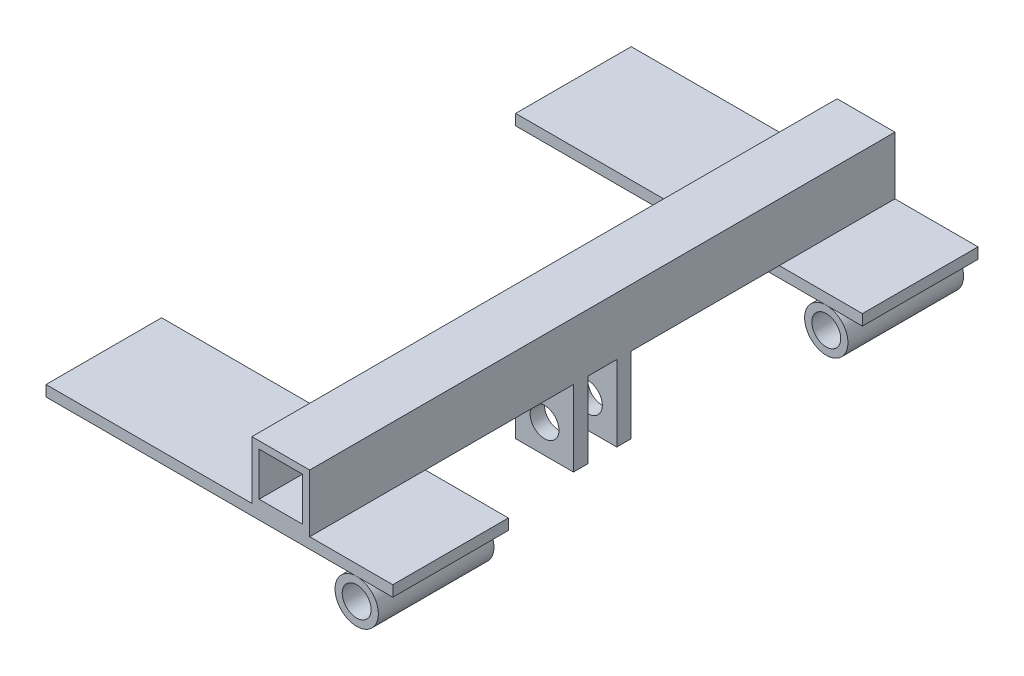
SolidWorks part; units mm, degrees
ref_plane "Front" through (0, 0, 0) normal (0, 0, 1) x (1, 0, 0)
ref_plane "Top" through (0, 0, 0) normal (0, 1, 0) x (1, 0, 0)
ref_plane "Right" through (0, 0, 0) normal (1, 0, 0) x (0, 0, -1)
sketch "Sketch1" plane through (0, 0, 0) normal (0, 0, 1) x (1, 0, 0)
  circle A0 centre (0, 0) radius 19.05
  circle A1 centre (0, 0) radius 12.7
  dimension "D1" = 38.1
  dimension "D2" = 25.4
extrude "Extrude1" add sketch "Sketch1" along normal mid plane 514.35
ref_plane "Plane1" through (0, 19.05, 0) normal (0, 1, 0) x (-1, 0, 0)
sketch "Sketch2" plane through (0, 19.05, 0) normal (0, 1, 0) x (-1, 0, 0)
  line L0 (0, 0) -> (341.5681, 0) construction
  line L1 (-31.75, 257.175) -> (273.05, 257.175)
  line L2 (-31.75, 257.175) -> (-31.75, 155.575)
  line L3 (-31.75, 155.575) -> (273.05, 155.575)
  line L4 (273.05, 257.175) -> (273.05, 155.575)
  line L5 (-31.75, -155.575) -> (273.05, -155.575)
  line L6 (-31.75, -155.575) -> (-31.75, -257.175)
  line L7 (-31.75, -257.175) -> (273.05, -257.175)
  line L8 (273.05, -155.575) -> (273.05, -257.175)
  line L9 (-19.05, 257.175) -> (-19.05, -257.175) construction
  line L10 (19.05, 257.175) -> (-19.05, 257.175) construction
  line L11 (-19.05, -257.175) -> (19.05, -257.175) construction
  dimension "D1" = 304.8
  dimension "D2" = 12.7
  dimension "D3" = 101.6
extrude "Extrude2" add sketch "Sketch2" along normal blind 9.525
sketch "Sketch3" plane through (0, 0, 0) normal (0, 0, 1) x (1, 0, 0)
  line L1 (-92.075, 28.575) -> (-92.075, -38.1)
  line L2 (-92.075, -38.1) -> (-41.275, -38.1)
  line L3 (-41.275, -38.1) -> (-41.275, 28.575)
  line L4 (-273.05, 28.575) -> (31.75, 28.575) construction
  line L5 (-92.075, 28.575) -> (-41.275, 28.575)
  line L6 (-66.675, -38.1) -> (-66.675, -12.7) construction
  circle A0 centre (-66.675, -12.7) radius 12.7
  dimension "D1" = 25.4
  dimension "D2" = 66.675
  dimension "D3" = 50.8
  dimension "D4" = 25.4
  dimension "D5" = 66.675
  dimension "D6" = 12.7
extrude "Extrude3" add sketch "Sketch3" along normal mid plane 50.8
sketch "Sketch4" plane through (0, 28.575, 0) normal (0, 1, 0) x (-1, 0, 0)
  line L0 (41.275, 25.4) -> (41.275, -25.4) construction
  line L1 (41.275, -12.7) -> (92.075, -12.7)
  line L2 (41.275, -12.7) -> (41.275, 12.7)
  line L3 (41.275, 12.7) -> (92.075, 12.7)
  line L4 (92.075, -12.7) -> (92.075, 12.7)
  line L5 (92.075, 25.4) -> (92.075, -25.4) construction
  line L6 (0, 0) -> (92.075, 0) construction
  dimension "D1" = 25.4
extrude "Cut-Extrude1" cut sketch "Sketch4" against normal up to next (66.675 mm away)
sketch "Sketch5" plane through (0, 0, 0) normal (0, 1, 0) x (1, 0, 0)
  line L0 (-273.05, 155.575) -> (31.75, 155.575) construction
  line L1 (-19.05, 155.575) -> (19.05, 155.575)
  line L2 (-19.05, 155.575) -> (-19.05, -155.575)
  line L3 (-19.05, -155.575) -> (19.05, -155.575)
  line L4 (19.05, 155.575) -> (19.05, -155.575)
  line L5 (-19.05, 257.175) -> (-19.05, -257.175) construction
  line L6 (31.75, -155.575) -> (-273.05, -155.575) construction
  line L7 (19.05, -257.175) -> (19.05, 257.175) construction
extrude "Cut-Extrude2" cut sketch "Sketch5" against normal through all and the other way through all
sketch "Sketch7" plane through (0, 0, 0) normal (0, 0, 1) x (1, 0, 0)
  line L0 (-273.05, 28.575) -> (31.75, 28.575) construction
  line L1 (-92.075, 79.375) -> (-41.275, 79.375)
  line L2 (-92.075, 79.375) -> (-92.075, 28.575)
  line L3 (-92.075, 28.575) -> (-41.275, 28.575)
  line L4 (-41.275, 79.375) -> (-41.275, 28.575)
  line L5 (-66.675, -38.1) -> (-66.675, 79.375) construction
  line L6 (-85.725, 73.025) -> (-47.625, 73.025)
  line L7 (-85.725, 73.025) -> (-85.725, 34.925)
  line L8 (-85.725, 34.925) -> (-47.625, 34.925)
  line L9 (-47.625, 73.025) -> (-47.625, 34.925)
  line L10 (-92.075, -38.1) -> (-41.275, -38.1) construction
  line L11 (-92.075, 53.975) -> (-41.275, 53.975) construction
  dimension "D1" = 50.8
  dimension "D2" = 6.35
extrude "Extrude4" add sketch "Sketch7" along normal up to surface and the other way up to surface
